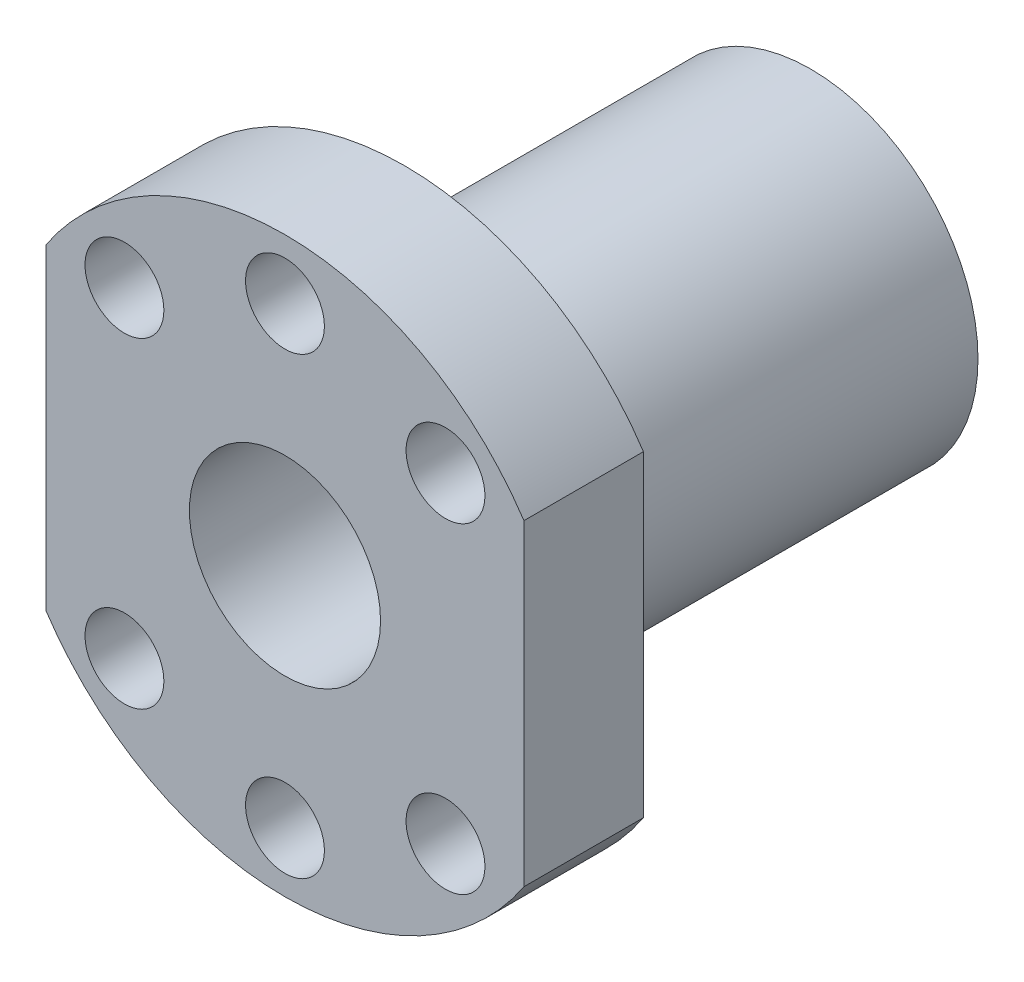
SolidWorks part; units mm, degrees
material "1.0037 (S235JR)"
ref_plane "Płaszczyzna przednia" through (0, 0, 0) normal (0, 0, 1) x (1, 0, 0)
ref_plane "Płaszczyzna górna" through (0, 0, 0) normal (0, 1, 0) x (1, 0, 0)
ref_plane "Płaszczyzna prawa" through (0, 0, 0) normal (1, 0, 0) x (0, 0, -1)
sketch "Szkic1" plane through (0, 0, 0) normal (1, 0, 0) x (0, 0, -1)
  line L0 (0, 0) -> (44, 0)
  line L1 (44, 0) -> (44, 14)
  line L2 (44, 14) -> (10, 14)
  line L3 (10, 14) -> (10, 24)
  line L4 (10, 24) -> (0, 24)
  line L5 (0, 24) -> (0, 0)
  dimension "D1" = 14
  dimension "D2" = 10
  dimension "D3" = 44
  dimension "D4" = 24
revolve "Obrót1" add sketch "Szkic1" angle 360 about L0
sketch "Szkic2" plane through (0, 0, 0) normal (0, 0, 1) x (1, 0, 0)
  line L0 (-20, 13.2665) -> (-20, -13.2665)
  line L1 (20, -13.2665) -> (20, 13.2665)
  circle A0 centre (0, 0) radius 24 construction
  arc A1 (-20, 13.2665) -> (-20, -13.2665) centre (0, 0) ccw
  arc A2 (20, -13.2665) -> (20, 13.2665) centre (0, 0) ccw
  circle A3 centre (0, 0) radius 19 construction
  circle A4 centre (-13.435, 13.435) radius 3.3
  circle A5 centre (0, 19) radius 3.3
  circle A6 centre (13.435, 13.435) radius 3.3
  circle A7 centre (0, 0) radius 8
  dimension "D3" = 16
  dimension "D4" = 38
  dimension "D7" = 6.6
  dimension "D1" = 40
  dimension "D2" = 20
  dimension "D5" = 45
  dimension "D6" = 45
extrude "Wytnij-wyciągnięcie1" cut sketch "Szkic2" against normal through all
mirror "Lustro1" about plane through (0, 0, 0) normal (0, 1, 0) of "Wytnij-wyciągnięcie1"
